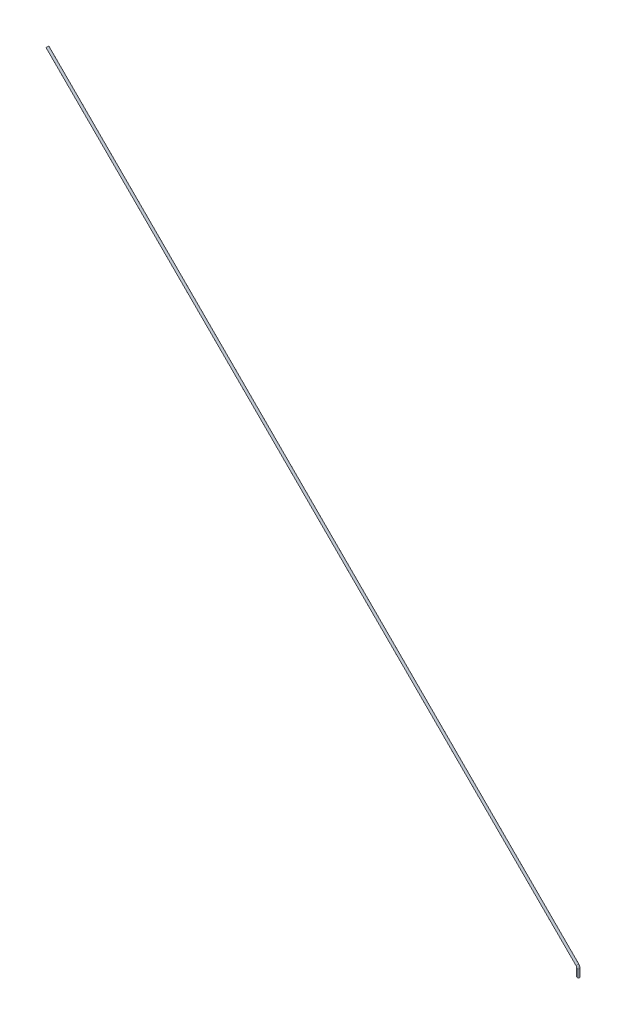
SolidWorks part; units mm, degrees
ref_plane "Front Plane" through (0, 0, 0) normal (0, 0, 1) x (1, 0, 0)
ref_plane "Top Plane" through (0, 0, 0) normal (0, 1, 0) x (1, 0, 0)
ref_plane "Right Plane" through (0, 0, 0) normal (1, 0, 0) x (0, 0, -1)
ref_plane "Plane1" through (-1.2197, 1.2197, 0) normal (-0.7071, 0.7071, 0) x (-0.7071, -0.7071, 0)
sketch "Sketch1" plane through (-1.2197, 1.2197, 0) normal (-0.7071, 0.7071, 0) x (-0.7071, -0.7071, 0)
  line L0 (-0.6642, -0.25) -> (-0.6642, 0.25) construction
  circle A0 centre (-1.4142, 0) radius 0.25
  dimension "D1" = 0.5
revolve "Revolve1" add sketch "Sketch1" angle 45 about L0
sketch "Sketch2" plane through (0, 1.6893, 0) normal (0, -1, 0) x (1, 0, 0)
  circle A0 centre (0, 0) radius 0.25
extrude "Boss-Extrude1" add sketch "Sketch2" along normal blind 1.6893
sketch "Sketch3" plane through (-1.2197, 1.2197, 0) normal (-0.7071, 0.7071, 0) x (0, 0, 1)
  circle A0 centre (0, 1.4142) radius 0.25
extrude "Boss-Extrude2" add sketch "Sketch3" along normal blind 162.6893
